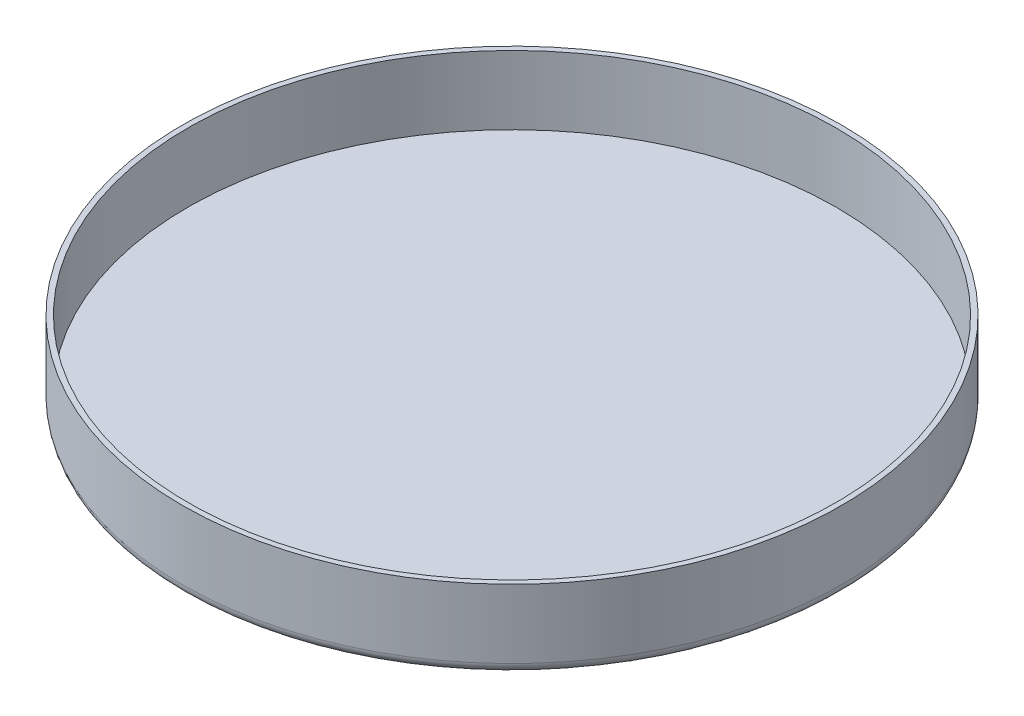
SolidWorks part; units mm, degrees
ref_plane "Front Plane" through (0, 0, 0) normal (0, 0, 1) x (1, 0, 0)
ref_plane "Top Plane" through (0, 0, 0) normal (0, 1, 0) x (1, 0, 0)
ref_plane "Right Plane" through (0, 0, 0) normal (1, 0, 0) x (0, 0, -1)
sketch "Sketch1" plane through (0, 0, 0) normal (0, 1, 0) x (1, 0, 0)
  circle A0 centre (0, 0) radius 77.978
  circle A1 centre (0, 0) radius 79.248
  dimension "D1" = 155.956
  dimension "D2" = 158.496
extrude "Boss-Extrude1" add sketch "Sketch1" along normal blind 19.05
sketch "Sketch2" plane through (0, 0, 0) normal (0, 1, 0) x (1, 0, 0)
  circle A0 centre (0, 0) radius 77.978
extrude "Boss-Extrude2" add sketch "Sketch2" along normal blind 2.54
fillet "Fillet1" radius 2.54 1 edges at (0, 0, 79.248)
